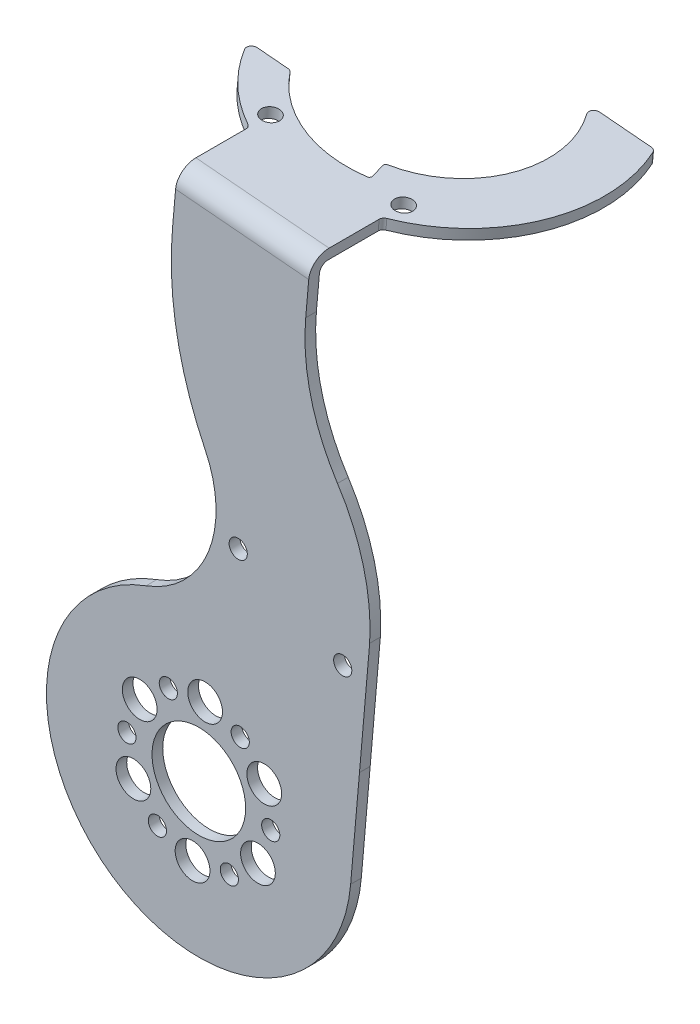
SolidWorks part; units mm, degrees
ref_plane "前视基准面" through (0, 0, 0) normal (0, 0, 1) x (1, 0, 0)
ref_plane "上视基准面" through (0, 0, 0) normal (0, 1, 0) x (1, 0, 0)
ref_plane "右视基准面" through (0, 0, 0) normal (1, 0, 0) x (0, 0, -1)
ref_plane "基准面1" through (0, 0, 2) normal (0, 0, 1) x (1, 0, 0)
sketch "草图1" plane through (0, 0, 2) normal (0, 0, 1) x (1, 0, 0)
  line L0 (19.9914, 85.0814) -> (20.6887, 93.051)
  line L1 (20.6887, 93.051) -> (-4.2162, 95.2298)
  line L2 (-4.2162, 95.2298) -> (-4.9135, 87.2603)
  line L3 (28.3915, -2.4839) -> (30.0475, 16.4438)
  line L4 (30.0475, 16.4438) -> (31.9502, 38.3355)
  arc A0 (-4.9135, 87.2603) -> (1.1989, 54.271) centre (57.6328, 81.7882) ccw
  arc A1 (1.1989, 54.271) -> (-9.8592, 26.7404) centre (-16.7779, 45.5055) cw
  arc A2 (-9.8592, 26.7404) -> (28.3915, -2.4839) centre (0, 0) ccw
  arc A3 (31.9502, 38.3355) -> (25.9346, 61.2226) centre (-5.7636, 40.657) ccw
  arc A4 (25.9346, 61.2226) -> (19.9914, 85.0814) centre (57.6328, 81.7882) cw
extrude "凸台-拉伸1" add sketch "草图1" against normal blind 2
sketch "草图2" plane through (8.2362, 94.1404, 0) normal (0.0872, 0.9962, 0) x (-0.9962, 0.0872, 0)
  line L0 (-15.4919, -49.1) -> (-25.8505, -49.1)
  line L1 (-12.5, -11.4875) -> (-12.5, 2)
  line L2 (-12.5, 2) -> (12.5, 2)
  line L3 (12.5, 2) -> (12.5, -11.4875)
  line L4 (23.6696, -24.1) -> (17.4374, -24.1)
  line L5 (-5.6293, -16.0911) -> (-4.6587, -19.7133)
  arc A0 (-25.8505, -49.1) -> (-12.5, -11.4875) centre (0, -37.1) cw
  arc A1 (12.5, -11.4875) -> (24.5303, -22.5909) centre (0, -37.1) cw
  arc A2 (24.5303, -22.5909) -> (23.6696, -24.1) centre (23.6696, -23.1) cw
  arc A3 (17.4374, -24.1) -> (-5.6293, -16.0911) centre (0, -37.1) ccw
  arc A4 (-4.6587, -19.7133) -> (-14.6766, -47.5211) centre (0, -37.1) ccw
  arc A5 (-14.6766, -47.5211) -> (-15.4919, -49.1) centre (-15.4919, -48.1) cw
extrude "凸台-拉伸2" add sketch "草图2" along normal blind 2
hole_wizard "Ø6.5 (6.5) 直径孔1" positions "草图4" profile "草图3" hole size "Ø6.5" standard "ANSI Metric"
sketch "草图4" plane through (0, 0, 2) normal (0, 0, 1) x (1, 0, 0)
  point P0 (11.0586, -7.7433)
  point P1 (1.1766, 13.4486)
  point P2 (-12.2352, -5.7053)
  point P3 (-11.0586, 7.7433)
  point P4 (12.2352, 5.7053)
  point P5 (-1.1766, -13.4486)
sketch "草图3" plane through (11.0586, -7.7433, 2) normal (1, 0, 0) x (0, -1, 0)
  line L0 (0, 0) -> (0, 51.1)
  line L1 (0, 51.1) -> (3.25, 51.1)
  line L2 (3.25, 51.1) -> (3.25, 0)
  line L5 (3.25, 0) -> (0, 0)
  line L11 (0, -6.35) -> (0, 107.95) construction
  dimension "通孔孔直径" = 6.5
  dimension "通孔孔深度" = 51.1
hole_wizard "Ø3.4 (3.4) 直径孔1" positions "草图6" profile "草图5" hole size "Ø3.4" standard "ANSI Metric"
sketch "草图6" plane through (0, 0, 2) normal (0, 0, 1) x (1, 0, 0)
  point P0 (13.4486, -1.1766)
  point P1 (-5.7053, 12.2352)
  point P2 (-7.7433, -11.0586)
  point P3 (-13.4486, 1.1766)
  point P4 (7.7433, 11.0586)
  point P5 (5.7053, -12.2352)
  point P6 (26.9127, 32.2445)
  point P7 (7.3669, 41.3489)
sketch "草图5" plane through (13.4486, -1.1766, 2) normal (1, 0, 0) x (0, -1, 0)
  line L0 (0, 0) -> (0, 51.1)
  line L1 (0, 51.1) -> (1.7, 51.1)
  line L2 (1.7, 51.1) -> (1.7, 0)
  line L5 (1.7, 0) -> (0, 0)
  line L11 (0, -6.35) -> (0, 107.95) construction
  dimension "通孔孔直径" = 3.4
  dimension "通孔孔深度" = 51.1
hole_wizard "Ø17.5 (17.5) 直径孔1" positions "草图8" profile "草图7" hole size "Ø17.5" standard "ANSI Metric"
sketch "草图8" plane through (0, 0, 2) normal (0, 0, 1) x (1, 0, 0)
  point P0 (0, 0)
sketch "草图7" plane through (0, 0, 2) normal (1, 0, 0) x (0, -1, 0)
  line L0 (0, 0) -> (0, 51.1)
  line L1 (0, 51.1) -> (8.75, 51.1)
  line L2 (8.75, 51.1) -> (8.75, 0)
  line L5 (8.75, 0) -> (0, 0)
  line L11 (0, -6.35) -> (0, 107.95) construction
  dimension "通孔孔直径" = 17.5
  dimension "通孔孔深度" = 51.1
hole_wizard "Ø3.4 (3.4) 直径孔2" positions "草图10" profile "草图9" hole size "Ø3.4" standard "ANSI Metric"
sketch "草图10" plane through (8.2362, 94.1404, 0) normal (-0.0872, -0.9962, 0) x (0.9962, -0.0872, 0)
  point P0 (-25, 37.1)
  point P1 (-12.5, -15.4494)
  point P2 (12.5, -15.4494)
sketch "草图9" plane through (-16.6686, 96.3193, 37.1) normal (0, 0, 1) x (0.9962, -0.0872, 0)
  line L0 (0, 0) -> (0, 6.6164)
  line L1 (0, 6.6164) -> (1.7, 6.6164)
  line L2 (1.7, 6.6164) -> (1.7, 0)
  line L5 (1.7, 0) -> (0, 0)
  line L11 (0, -6.35) -> (0, 107.95) construction
  dimension "通孔孔直径" = 3.4
  dimension "通孔孔深度" = 6.6164
fillet "圆角1" radius 0.5 2 edges at (12.9644, 94.7306, -19.7133) (13.9313, 94.646, -16.0911)
fillet "圆角2" radius 1 4 edges at (-9.0477, 96.6564, -24.1) (-4.1291, 96.226, -11.4875) (34.0755, 92.8836, -49.1) (20.7758, 94.0471, -11.4875)
fillet "圆角3" radius 1.5 1 edges at (8.2362, 94.1404, 0)
fillet "圆角4" radius 3.5 1 edges at (8.4105, 96.1328, 2)
